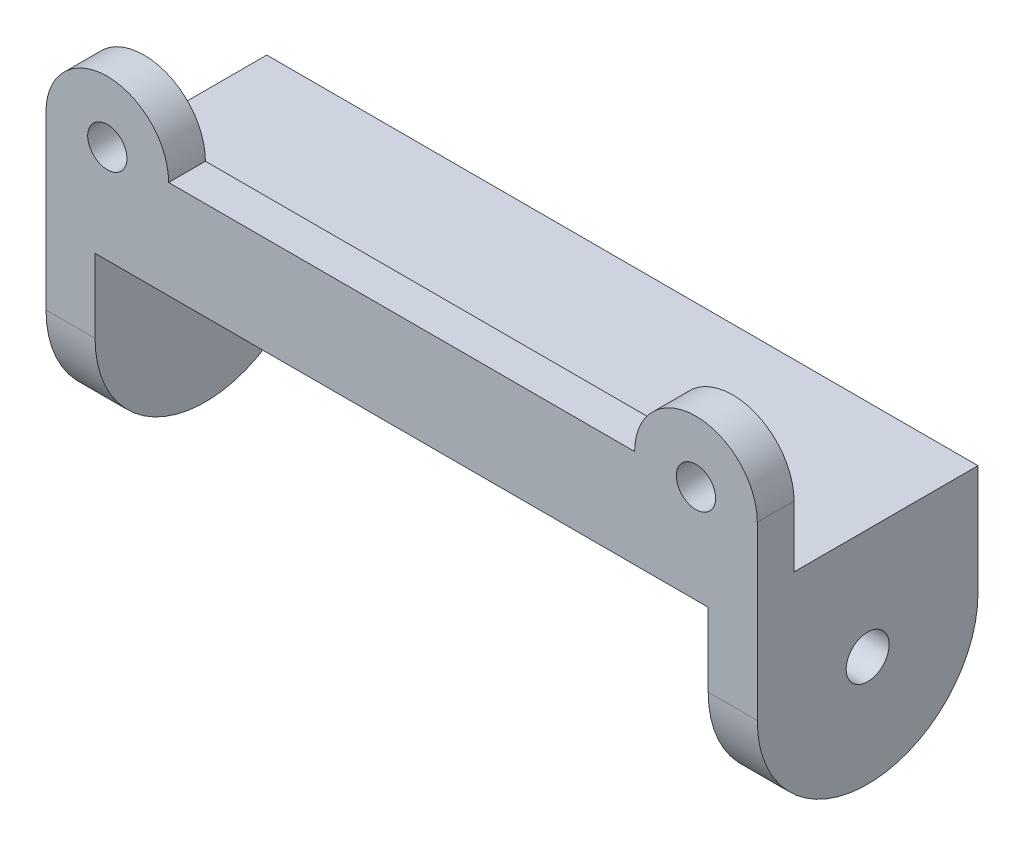
SolidWorks part; units mm, degrees
ref_plane "前视基准面" through (0, 0, 0) normal (0, 0, 1) x (1, 0, 0)
ref_plane "上视基准面" through (0, 0, 0) normal (0, 1, 0) x (1, 0, 0)
ref_plane "右视基准面" through (0, 0, 0) normal (1, 0, 0) x (0, 0, -1)
sketch "草图3" plane through (0, 0, 0) normal (0, 0, 1) x (1, 0, 0)
  line L0 (-24, 0) -> (24, 0) construction
  line L1 (-29, 0) -> (-29, -5)
  line L2 (-29, -5) -> (29, -5)
  line L3 (29, -5) -> (29, 0)
  line L4 (-19, 0) -> (19, 0)
  circle A0 centre (-24, 0) radius 1.6
  circle A1 centre (24, 0) radius 1.6
  arc A2 (-19, 0) -> (-29, 0) centre (-24, 0) ccw
  arc A3 (29, 0) -> (19, 0) centre (24, 0) ccw
  point P4 (0, 0)
  dimension "D1" = 3.2
  dimension "D3" = 10
  dimension "D2" = 48
  dimension "D4" = 5
  dimension "D5" = 58
extrude "凸台-拉伸2" add sketch "草图3" along normal blind 3
sketch "草图4" plane through (0, 0, 3) normal (0, 0, 1) x (1, 0, 0)
  line L1 (-29, -5) -> (29, -5)
  line L2 (-29, -5) -> (-29, -8)
  line L3 (-29, -8) -> (29, -8)
  line L4 (29, -5) -> (29, -8)
  dimension "D1" = 3
extrude "凸台-拉伸3" add sketch "草图4" against normal blind 18
sketch "草图5" plane through (29, 0, 0) normal (1, 0, 0) x (0, 0, -1)
  line L0 (-3, -8) -> (-3, -14)
  line L1 (15, -8) -> (15, -14)
  line L2 (15, -5) -> (0, -5) construction
  line L3 (-3, -8) -> (15, -8)
  arc A0 (-3, -14) -> (15, -14) centre (6, -14) ccw
  circle A1 centre (6, -14) radius 1.75
  dimension "D1" = 3.5
extrude "凸台-拉伸4" add sketch "草图5" against normal blind 4
sketch "草图6" plane through (25, 0, 0) normal (-1, 0, 0) x (0, 0, 1)
  line L1 (-9, -11) -> (-3, -11)
  line L2 (-9, -11) -> (-9, -17)
  line L3 (-9, -17) -> (-3, -17)
  line L4 (-3, -11) -> (-3, -17)
  line L5 (-9, -11) -> (-3, -17) construction
  line L6 (-9, -17) -> (-3, -11) construction
  point P0 (-6, -14)
  dimension "D1" = 6
  dimension "D2" = 6
mirror "镜向1" about plane through (0, 0, 0) normal (1, 0, 0) of "凸台-拉伸4"
sketch "草图7" plane through (25, 0, 0) normal (-1, 0, 0) x (0, 0, 1)
  circle A0 centre (-6, -14) radius 8
  dimension "D1" = 16
extrude "切除-拉伸2" cut sketch "草图7" along normal up to surface (50 mm away) up to face at (-25, -13.25, -6)
